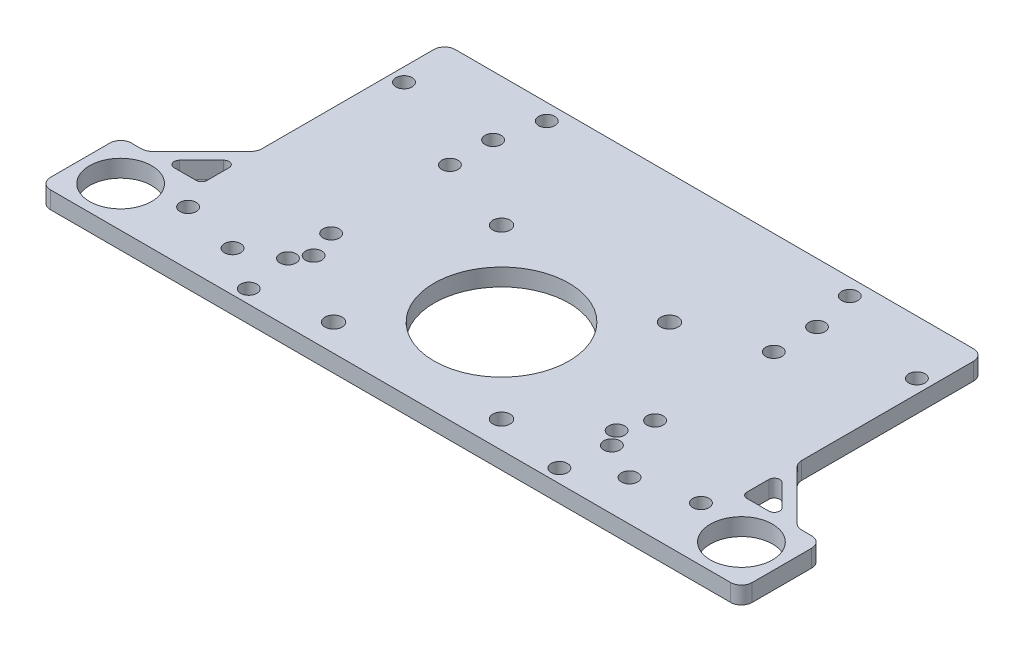
SolidWorks part; units mm, degrees
ref_plane "前视基准面" through (0, 0, 0) normal (0, 0, 1) x (1, 0, 0)
ref_plane "上视基准面" through (0, 0, 0) normal (0, 1, 0) x (1, 0, 0)
ref_plane "右视基准面" through (0, 0, 0) normal (1, 0, 0) x (0, 0, -1)
other "Configuration Table"
sketch "草图1" plane through (0, 0, 0) normal (0, 1, 0) x (1, 0, 0)
  line L0 (0, 30) -> (0, -30) construction
  line L1 (-50, 30) -> (50, 30)
  line L2 (-50, 30) -> (-50, -30)
  line L3 (-50, -30) -> (50, -30)
  line L4 (50, 30) -> (50, -30)
  line L5 (-50, -30) -> (-65, -30)
  line L6 (-50, 0) -> (50, 0) construction
  line L7 (-65, -30) -> (-65, -15)
  line L8 (-65, -15) -> (-50, -15)
  line L9 (-50, -15) -> (-50, -30)
  line L10 (50, -15) -> (50, -30)
  line L11 (65, -15) -> (50, -15)
  line L12 (65, -30) -> (65, -15)
  line L13 (50, -30) -> (65, -30)
  line L14 (-57.5, -15) -> (-50, -7.5)
  line L16 (-60.3284, -15) -> (-50, -4.6716)
  line L17 (-60.3284, -15) -> (-57.5, -15)
  line L18 (-50, -4.6716) -> (-50, -7.5)
  line L19 (60.3284, -15) -> (50, -4.6716)
  line L20 (60.3284, -15) -> (57.5, -15)
  line L21 (57.5, -15) -> (50, -7.5)
  line L22 (50, -4.6716) -> (50, -7.5)
  dimension "D1" = 60
  dimension "D2" = 100
  dimension "D3" = 15
  dimension "D4" = 15
  dimension "D5" = 45
  dimension "D6" = 2
extrude "凸台-拉伸1" add sketch "草图1" along normal blind 3.2 contours L8 L7 L5 L2 | L4 L1 L2 L3 | L16 L8 L14 L2 | L4 L13 L12 L11 | L21 L11 L19 L4
sketch "草图2" plane through (0, 3.2, 0) normal (0, 1, 0) x (1, 0, 0)
  line L0 (0, 0) -> (0, -30) construction
  line L1 (-65, -22.5) -> (-50, -22.5) construction
  line L2 (0, 0) -> (0, 30) construction
  line L3 (-65, -30) -> (-65, -15) construction
  line L4 (-15.5563, -25) -> (15.5563, -25) construction
  line L5 (0, -9.4437) -> (0, -25) construction
  line L6 (-50, 0) -> (50, 0) construction
  line L7 (-65, -30) -> (-50, -30)
  line L8 (-57.5, -30) -> (-57.5, -22.5) construction
  line L9 (-47.5, 30) -> (-47.5, -30) construction
  line L10 (-50, -20) -> (50, -20) construction
  line L11 (-50, 20) -> (50, 20) construction
  line L12 (-50, -7.5) -> (-50, -15) construction
  line L13 (-50, -15) -> (-50, -30) construction
  line L14 (65, -30) -> (-65, -30) construction
  line L15 (50, -7.5) -> (50, -15) construction
  line L16 (50, -15) -> (50, -30) construction
  line L17 (-50, -30) -> (50, -30)
  line L18 (0, -20.4671) -> (0, 20.4671) construction
  line L19 (-50, 30) -> (-50, -30) construction
  line L20 (-50, 30) -> (50, 30)
  line L21 (-95.0755, 0) -> (95.0755, 0) construction
  line L22 (50, 30) -> (50, -4.6716) construction
  line L23 (30, -30) -> (30, 30) construction
  line L24 (-28.065, 27) -> (-28.065, -16.18) construction
  circle A0 centre (0, -9.4437) radius 12.5
  circle A1 centre (15.5563, -25) radius 1.6
  circle A2 centre (15.5563, 6.1127) radius 1.6
  circle A3 centre (-15.5563, 6.1127) radius 1.6
  circle A4 centre (-15.5563, -25) radius 1.6
  circle A5 centre (-47.5, 20) radius 1.5
  circle A6 centre (-47.5, -20) radius 1.5
  circle A7 centre (47.5, -20) radius 1.5
  circle A8 centre (47.5, 20) radius 1.5
  circle A17 centre (-57.5, -22.5) radius 5.75
  circle A18 centre (57.5, -22.5) radius 5.75
  circle A19 centre (30, 19) radius 1.5
  circle A20 centre (30, 11) radius 1.5
  circle A21 centre (-30, 11) radius 1.5
  circle A22 centre (-30, 19) radius 1.5
  circle A23 centre (30, -11) radius 1.5
  circle A24 centre (30, -19) radius 1.5
  circle A25 centre (-30, -19) radius 1.5
  circle A26 centre (-30, -11) radius 1.5
  circle A27 centre (-28.065, 27) radius 1.5
  circle A28 centre (28.065, 27) radius 1.5
  circle A29 centre (-28.065, -16.18) radius 1.5
  circle A30 centre (28.065, -16.18) radius 1.5
  circle A31 centre (-28.769, -27.5) radius 1.5
  circle A32 centre (28.769, -27.5) radius 1.5
  circle A33 centre (-36.769, -22.5) radius 1.5
  circle A34 centre (36.769, -22.5) radius 1.5
  point P6 (0, 30)
  point P62 (-50, 0)
  point P67 (0, -30)
  dimension "D1" = 25
  dimension "D2" = 3.2
  dimension "D6" = 3
  dimension "D7" = 3
  dimension "D12" = 20
  dimension "D15" = 11.5
  dimension "D18" = 3
  dimension "D19" = 3
  dimension "D13" = 3
  dimension "D14" = 3
  dimension "D25" = 3
  dimension "D29" = 3
  dimension "D30" = 3
  dimension "D33" = 3
  dimension "D3" = 22
  dimension "D5" = 5
  dimension "D8" = 20
  dimension "D9" = 20
  dimension "D10" = 2.5
  dimension "D11" = 20
  dimension "D16" = 49
  dimension "D17" = 41
  dimension "D20" = 11
  dimension "D21" = 19
  dimension "D22" = 17.5
  dimension "D23" = 95
  dimension "D24" = 40
  dimension "D26" = 43.18
  dimension "D27" = 3
  dimension "D28" = 56.13
  dimension "D31" = 57.538
  dimension "D32" = 2.5
  dimension "D34" = 7.5
  dimension "D35" = 8
  dimension "D4" = 4
extrude "切除-拉伸1" cut sketch "草图2" against normal up to surface (3.2 mm away) contours A17 | A18 | A27 | A25 A29 | A28 | A30 A24 up to face at (52.5, 0, 12.5)
fillet "圆角1" radius 2 10 edges at (65, 1.6, 30) (65, 1.6, 15) (-65, 1.6, 30) (-65, 1.6, 15) (-50, 1.6, -30) (50, 1.6, -30) (60.3284, 1.6, 15) (50, 1.6, 4.6716) (-60.3284, 1.6, 15) (-50, 1.6, 4.6716)
fillet "圆角2" radius 1 6 edges at (-50, 1.6, 15) (-50, 1.6, 7.5) (-57.5, 1.6, 15) (50, 1.6, 15) (57.5, 1.6, 15) (50, 1.6, 7.5)
